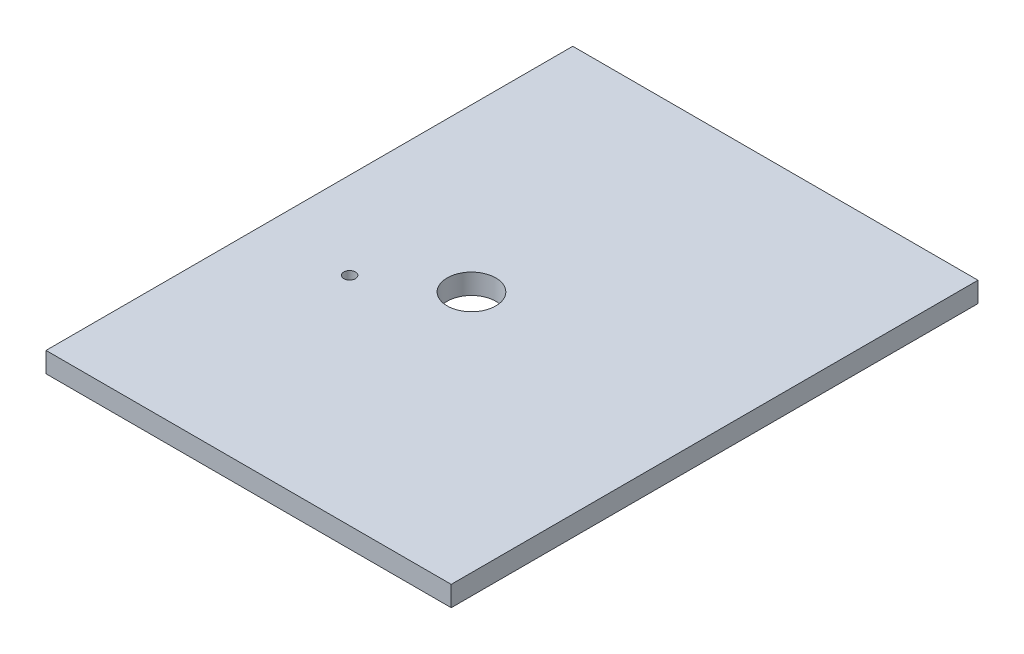
SolidWorks part; units mm, degrees
ref_plane "Front Plane" through (0, 0, 0) normal (0, 0, 1) x (1, 0, 0)
ref_plane "Top Plane" through (0, 0, 0) normal (0, 1, 0) x (1, 0, 0)
ref_plane "Right Plane" through (0, 0, 0) normal (1, 0, 0) x (0, 0, -1)
sketch "Sketch1" plane through (0, 0, 0) normal (0, 1, 0) x (1, 0, 0)
  line L0 (73.3491, 39.6462) -> (-26.6509, 39.6462) construction
  line L1 (-26.6509, 104.6462) -> (73.3491, 104.6462)
  line L2 (-26.6509, 104.6462) -> (-26.6509, -25.3538)
  line L3 (-26.6509, -25.3538) -> (73.3491, -25.3538)
  line L4 (73.3491, 104.6462) -> (73.3491, -25.3538)
  circle A0 centre (13.3491, 39.6462) radius 6
  circle A1 centre (-5.2352, 28.1657) radius 1.4442
  dimension "D3" = 12
  dimension "D1" = 130
  dimension "D2" = 100
  dimension "D4" = 40
extrude "Boss-Extrude1" add sketch "Sketch1" along normal blind 5
